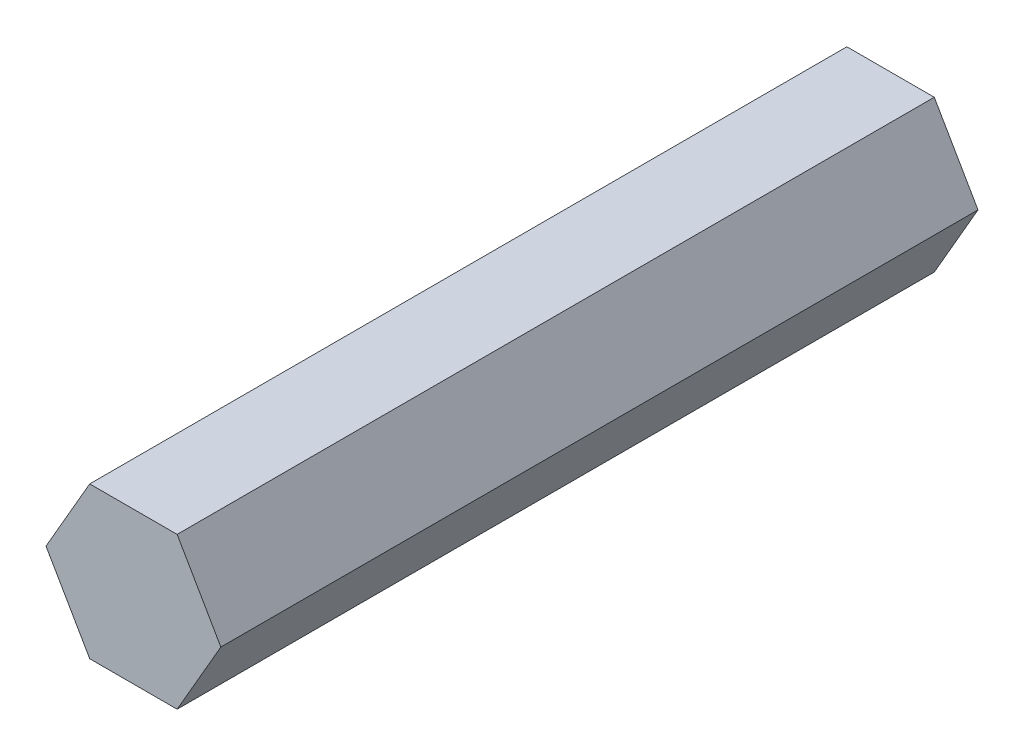
SolidWorks part; units mm, degrees
material "1060 Alloy"
ref_plane "Front Plane" through (0, 0, 0) normal (0, 0, 1) x (1, 0, 0)
ref_plane "Top Plane" through (0, 0, 0) normal (0, 1, 0) x (1, 0, 0)
ref_plane "Right Plane" through (0, 0, 0) normal (1, 0, 0) x (0, 0, -1)
sketch "Sketch1" plane through (0, 0, 0) normal (0, 0, 1) x (1, 0, 0)
  line L1 (7.3323, 0) -> (3.6662, 6.35)
  line L2 (3.6662, 6.35) -> (-3.6662, 6.35)
  line L3 (-3.6662, 6.35) -> (-7.3323, 0)
  line L4 (-7.3323, 0) -> (-3.6662, -6.35)
  line L5 (-3.6662, -6.35) -> (3.6662, -6.35)
  line L6 (3.6662, -6.35) -> (7.3323, 0)
  circle A0 centre (0, 0) radius 6.35 construction
  dimension "D1" = 12.7
extrude "Boss-Extrude1" add sketch "Sketch1" along normal blind 63.5
